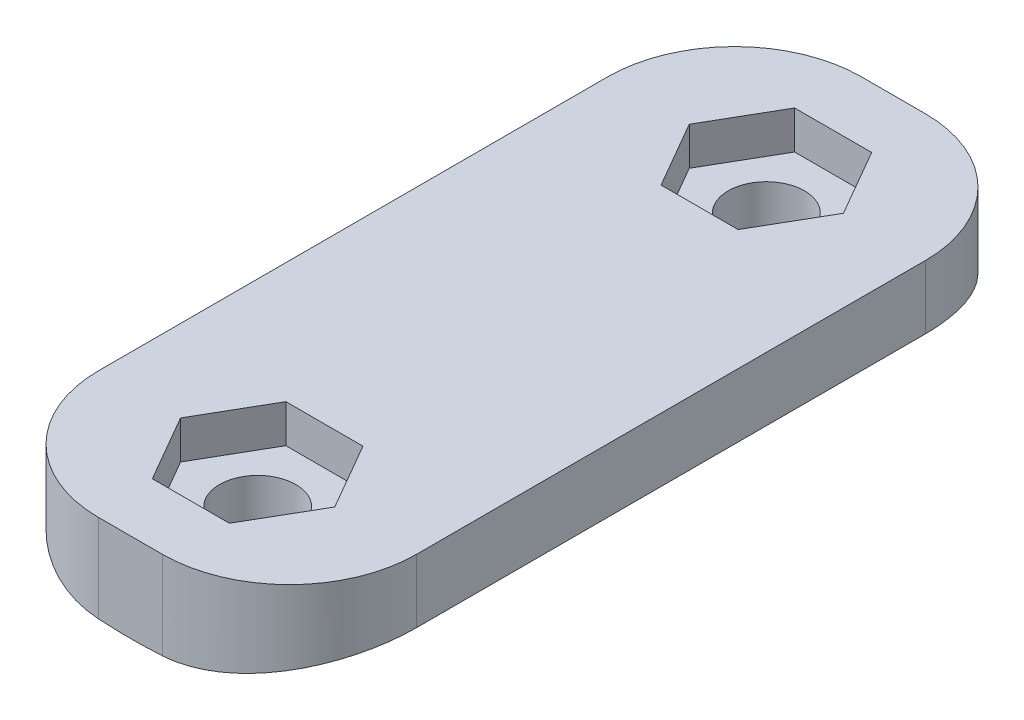
SolidWorks part; units mm, degrees
ref_plane "Спереди" through (0, 0, 0) normal (0, 0, 1) x (1, 0, 0)
ref_plane "Сверху" through (0, 0, 0) normal (0, 1, 0) x (1, 0, 0)
ref_plane "Справа" through (0, 0, 0) normal (1, 0, 0) x (0, 0, -1)
other "Configuration Table"
sketch "Эскиз1" plane through (0, 0, 0) normal (0, 0, 1) x (1, 0, 0)
  line L0 (-12.5, -38.2072) -> (-12.5, -33.2072)
  line L1 (12.5, -38.2072) -> (12.5, -33.2072)
  line L2 (12.5, -33.2072) -> (-12.5, -33.2072)
  arc A0 (-12.5, -38.2072) -> (12.5, -38.2072) centre (0, 0) ccw
  dimension "D1" = 40.2
  dimension "D2" = 5
  dimension "D3" = 25
extrude "Бобышка-Вытянуть1" add sketch "Эскиз1" along normal blind 60
sketch "Эскиз2" plane through (0, -33.2072, 0) normal (0, 1, 0) x (1, 0, 0)
  line L0 (0, 0) -> (0, -60) construction
  line L1 (12.5, 0) -> (-12.5, 0) construction
  line L2 (12.5, -60) -> (-12.5, -60) construction
  circle A0 centre (0, -10) radius 3
  circle A1 centre (0, -50) radius 3
  point P10 (0, 0)
  dimension "D1" = 6
  dimension "D2" = 10
  dimension "D3" = 10
extrude "Вырез-Вытянуть1" cut sketch "Эскиз2" against normal up to surface (6.9928 mm away)
sketch "Эскиз3" plane through (0, -33.2072, 0) normal (0, 1, 0) x (1, 0, 0)
  line L1 (3.0311, -4.75) -> (-3.0311, -4.75)
  line L2 (-3.0311, -4.75) -> (-6.0622, -10)
  line L3 (-6.0622, -10) -> (-3.0311, -15.25)
  line L4 (-3.0311, -15.25) -> (3.0311, -15.25)
  line L5 (3.0311, -15.25) -> (6.0622, -10)
  line L6 (6.0622, -10) -> (3.0311, -4.75)
  line L7 (3.0311, -44.75) -> (-3.0311, -44.75)
  line L8 (-3.0311, -44.75) -> (-6.0622, -50)
  line L9 (-6.0622, -50) -> (-3.0311, -55.25)
  line L10 (-3.0311, -55.25) -> (3.0311, -55.25)
  line L11 (3.0311, -55.25) -> (6.0622, -50)
  line L12 (6.0622, -50) -> (3.0311, -44.75)
  circle A0 centre (0, -10) radius 5.25 construction
  circle A1 centre (0, -50) radius 5.25 construction
  dimension "D1" = 10.5
extrude "Вырез-Вытянуть2" cut sketch "Эскиз3" against normal blind 3
fillet "Скругление1" radius 10 4 edges at (12.5, -35.7072, 60) (-12.5, -35.7072, 60) (-12.5, -35.7072, 0) (12.5, -35.7072, 0)
